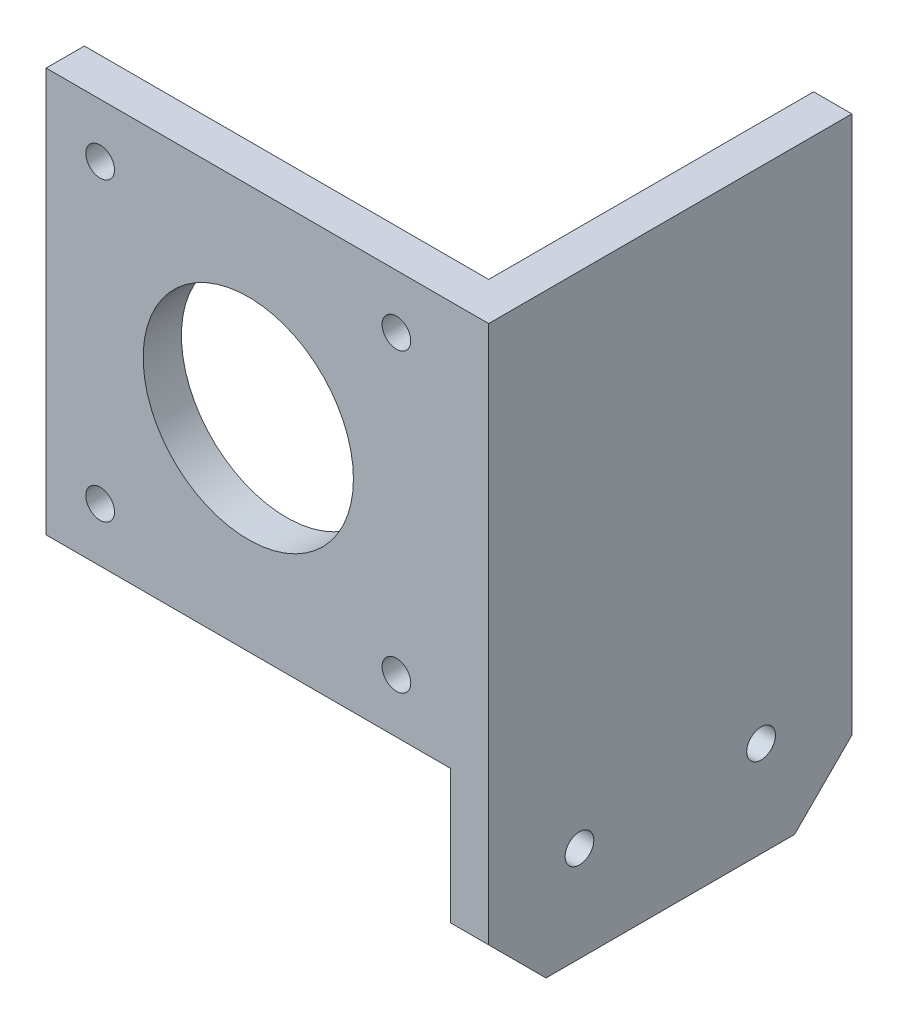
SolidWorks part; units mm, degrees
ref_plane "정면" through (0, 0, 0) normal (0, 0, 1) x (1, 0, 0)
ref_plane "윗면" through (0, 0, 0) normal (0, 1, 0) x (1, 0, 0)
ref_plane "우측면" through (0, 0, 0) normal (1, 0, 0) x (0, 0, -1)
sketch "스케치1" plane through (0, 0, 0) normal (0, 0, 1) x (1, 0, 0)
  line L0 (0, 21.15) -> (0, -21.15) construction
  line L1 (-21.15, -21.15) -> (21.15, -21.15)
  line L2 (-21.15, -21.15) -> (-21.15, 21.15)
  line L3 (-21.15, 21.15) -> (21.15, 21.15)
  line L4 (21.15, -21.15) -> (21.15, 21.15)
  line L5 (-21.15, -21.15) -> (21.15, 21.15) construction
  line L6 (-21.15, 21.15) -> (21.15, -21.15) construction
  line L7 (-21.15, 0) -> (21.15, 0) construction
  circle A0 centre (0, 0) radius 11
  circle A1 centre (-15.5, 15.5) radius 1.5
  circle A2 centre (15.5, 15.5) radius 1.5
  circle A3 centre (15.5, -15.5) radius 1.5
  circle A4 centre (-15.5, -15.5) radius 1.5
  point P0 (0, 0)
  dimension "D2" = 3
  dimension "D3" = 22
  dimension "D1" = 42.3
  dimension "D4" = 31
extrude "보스-돌출1" add sketch "스케치1" along normal blind 4
sketch "스케치2" plane through (21.15, 0, 0) normal (1, 0, 0) x (0, 0, -1)
  line L0 (-4, -21.15) -> (0, -21.15) construction
  line L1 (-4, 21.15) -> (34, 21.15)
  line L2 (-4, 21.15) -> (-4, -41.15)
  line L3 (-4, -41.15) -> (34, -41.15)
  line L4 (34, 21.15) -> (34, -41.15)
  line L5 (15, -41.15) -> (15, 21.15) construction
  line L6 (-4, -31.15) -> (34, -31.15) construction
  circle A0 centre (5.5, -31.15) radius 1.5
  circle A1 centre (24.5, -31.15) radius 1.5
  dimension "D3" = 3
  dimension "D1" = 20
  dimension "D2" = 34
  dimension "D4" = 19
extrude "보스-돌출2" add sketch "스케치2" along normal blind 4
chamfer "모따기1" distance 6 angle 45 2 edges at (23.15, -41.15, -34) (23.15, -41.15, 4)
